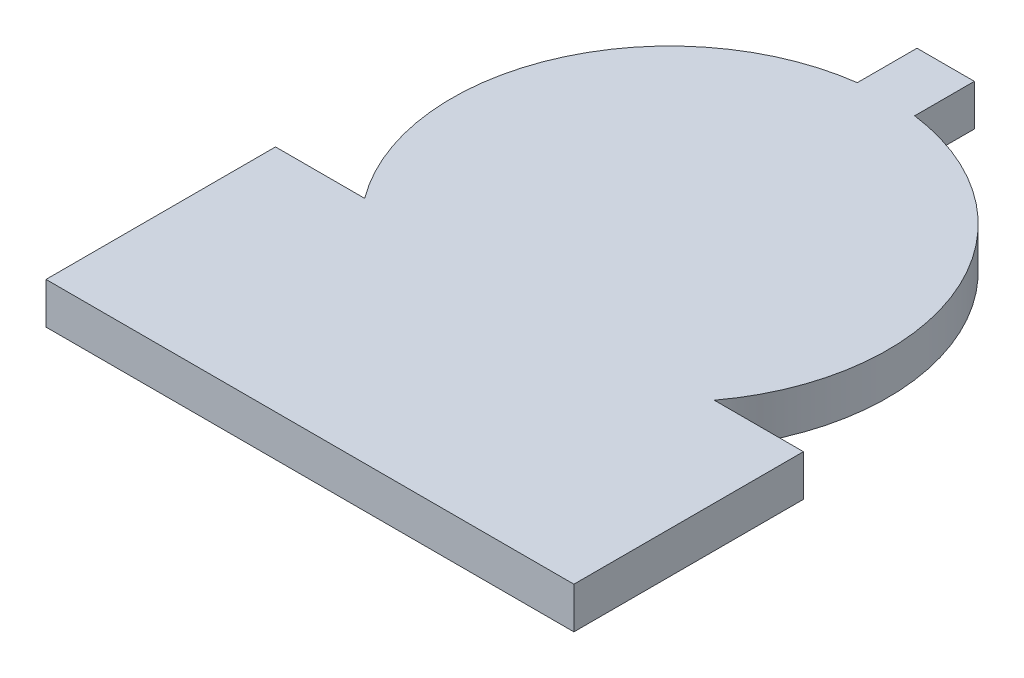
SolidWorks part; units mm, degrees
ref_plane "Front Plane" through (0, 0, 0) normal (0, 0, 1) x (1, 0, 0)
ref_plane "Top Plane" through (0, 0, 0) normal (0, 1, 0) x (1, 0, 0)
ref_plane "Right Plane" through (0, 0, 0) normal (1, 0, 0) x (0, 0, -1)
sketch "Sketch1" plane through (0, 0, 0) normal (0, 1, 0) x (1, 0, 0)
  line L0 (0, 0) -> (0, 24.13) construction
  line L1 (0, -24.7077) -> (0, -14.4282) construction
  line L2 (-3.175, 30.5242) -> (3.175, 30.5242)
  line L3 (-3.175, 30.5242) -> (-3.175, 23.9202)
  line L5 (3.175, 30.5242) -> (3.175, 23.9202)
  line L6 (-3.175, 30.5242) -> (0, 24.13) construction
  line L7 (0, 24.13) -> (3.175, 30.5242) construction
  line L8 (19.3413, -14.4282) -> (29.21, -14.4282) construction
  line L9 (19.3413, -14.4282) -> (29.21, -14.4282)
  line L10 (-29.21, -14.4282) -> (-19.3413, -14.4282)
  line L11 (-29.21, -14.4282) -> (-29.21, -39.8282)
  line L12 (-29.21, -39.8282) -> (29.21, -39.8282)
  line L13 (29.21, -14.4282) -> (29.21, -39.8282)
  line L14 (-29.21, -14.4282) -> (29.21, -39.8282) construction
  line L15 (-29.21, -39.8282) -> (29.21, -14.4282) construction
  line L16 (0, -14.4282) -> (29.21, -14.4282) construction
  arc A0 (19.3413, -14.4282) -> (3.175, 23.9202) centre (0, 0) ccw
  arc A1 (-3.175, 23.9202) -> (-19.3413, -14.4282) centre (0, 0) ccw
  point P6 (0, -27.1282)
  dimension "D1" = 48.26
  dimension "D2" = 6.35
  dimension "D3" = 6.604
  dimension "D4" = 29.21
  dimension "D5" = 25.4
extrude "Boss-Extrude1" add sketch "Sketch1" along normal blind 4.572
